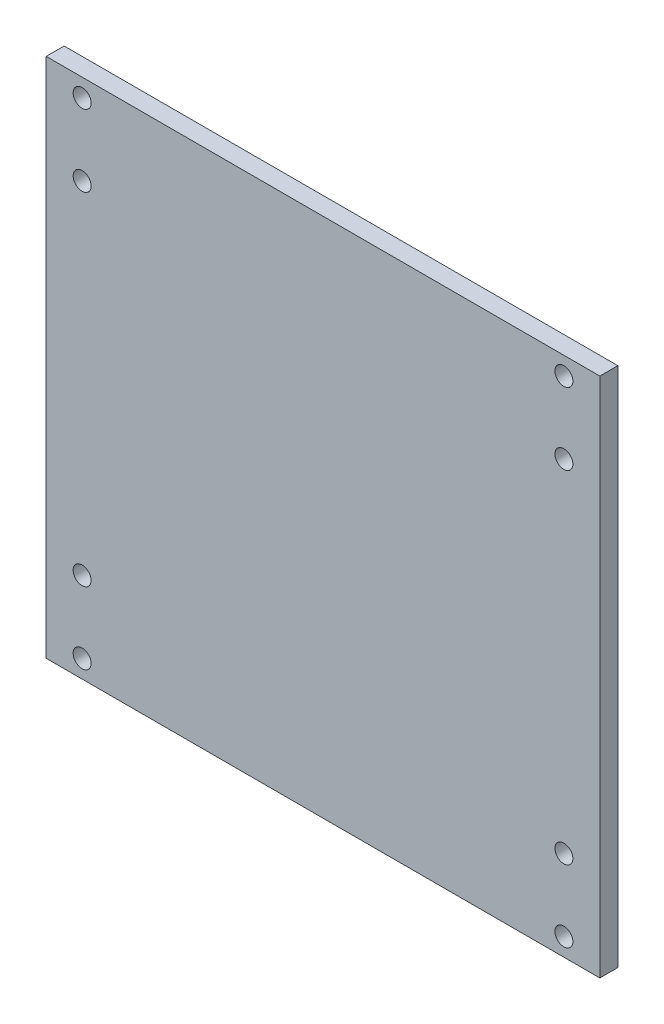
SolidWorks part; units mm, degrees
material "自訂塑膠"
ref_plane "前基準面" through (0, 0, 0) normal (0, 0, 1) x (1, 0, 0)
ref_plane "上基準面" through (0, 0, 0) normal (0, 1, 0) x (1, 0, 0)
ref_plane "右基準面" through (0, 0, 0) normal (1, 0, 0) x (0, 0, -1)
sketch "草圖1" plane through (0, 0, 0) normal (0, 0, 1) x (1, 0, 0)
  line L1 (-35.3072, 28.5639) -> (26.2928, 28.5639)
  line L2 (-35.3072, 28.5639) -> (-35.3072, -29.4361)
  line L3 (-35.3072, -29.4361) -> (26.2928, -29.4361)
  line L4 (26.2928, 28.5639) -> (26.2928, -29.4361)
  circle A0 centre (-31.3072, 26.5639) radius 1
  circle A1 centre (-31.3072, 18.5639) radius 1
  circle A2 centre (22.2928, 18.5639) radius 1
  circle A3 centre (22.2928, 26.5639) radius 1
  circle A4 centre (22.2928, -27.4361) radius 1
  circle A5 centre (22.2928, -19.4361) radius 1
  circle A6 centre (-31.3072, -19.4361) radius 1
  circle A7 centre (-31.3072, -27.4361) radius 1
  dimension "D3" = 8
  dimension "D4" = 2
  dimension "D5" = 2
  dimension "D6" = 4
  dimension "D7" = 8
  dimension "D8" = 2
  dimension "D9" = 8
  dimension "D10" = 2
  dimension "D1" = 58
  dimension "D2" = 61.6
extrude "填料-伸長1" add sketch "草圖1" along normal blind 2
